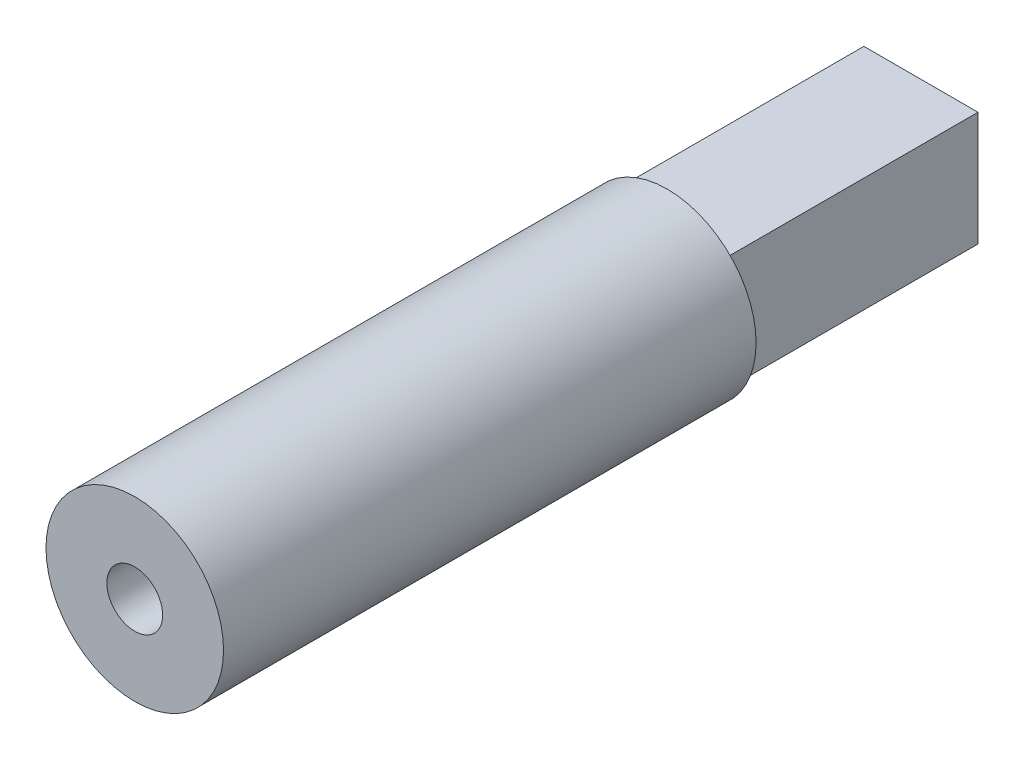
SolidWorks part; units mm, degrees
ref_plane "Front Plane" through (0, 0, 0) normal (0, 0, 1) x (1, 0, 0)
ref_plane "Top Plane" through (0, 0, 0) normal (0, 1, 0) x (1, 0, 0)
ref_plane "Right Plane" through (0, 0, 0) normal (1, 0, 0) x (0, 0, -1)
sketch "Sketch2" plane through (0, 0, 0) normal (0, 0, 1) x (1, 0, 0)
  circle A0 centre (0, 0) radius 3.5
extrude "Boss-Extrude1" add sketch "Sketch2" along normal blind 31
sketch "Sketch4" plane through (0, 0, 0) normal (0, 0, -1) x (-1, 0, 0)
  line L1 (-2.25, 2.25) -> (2.25, 2.25)
  line L2 (-2.25, 2.25) -> (-2.25, -2.25)
  line L3 (-2.25, -2.25) -> (2.25, -2.25)
  line L4 (2.25, 2.25) -> (2.25, -2.25)
  line L5 (-2.25, 2.25) -> (2.25, -2.25) construction
  line L6 (-2.25, -2.25) -> (2.25, 2.25) construction
  circle A1 centre (0, 0) radius 3.5
  circle A2 centre (0, 0) radius 3.5
  point P0 (0, 0)
  dimension "D1" = 4.5
  dimension "D2" = 4.5
  dimension "D3" = 0
extrude "Cut-Extrude1" cut sketch "Sketch4" against normal blind 10
sketch "Sketch7" plane through (0, 0, 31) normal (0, 0, 1) x (1, 0, 0)
  circle A0 centre (0, 0) radius 1.1
extrude "Cut-Extrude2" cut sketch "Sketch7" against normal blind 6
